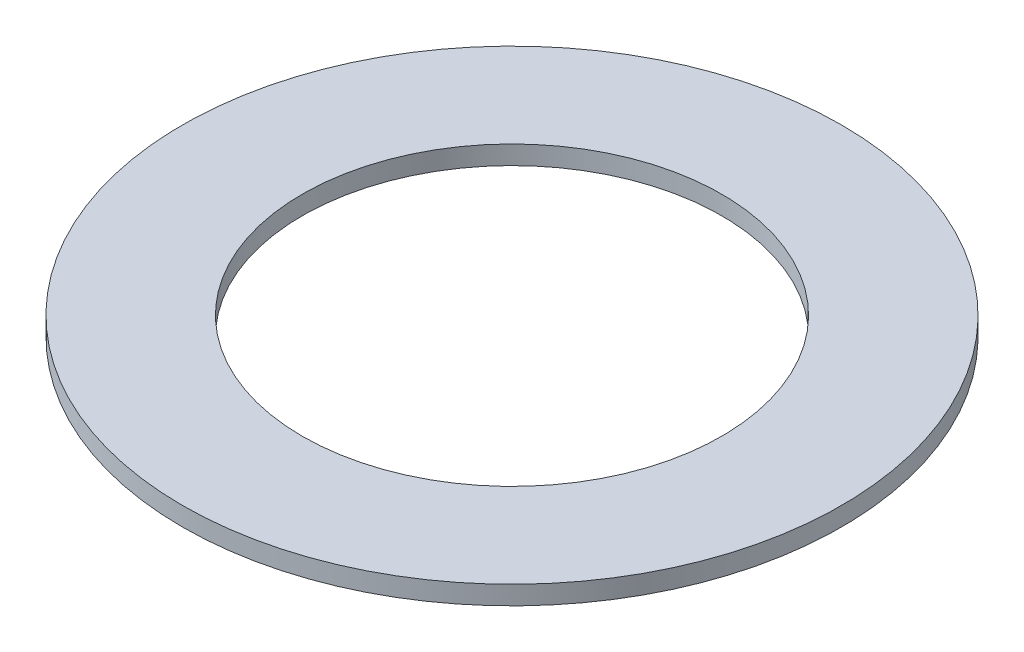
SolidWorks part; units mm, degrees
material "Chrome Stainless Steel"
ref_plane "Front Plane" through (0, 0, 0) normal (0, 0, 1) x (1, 0, 0)
ref_plane "Top Plane" through (0, 0, 0) normal (0, 1, 0) x (1, 0, 0)
ref_plane "Right Plane" through (0, 0, 0) normal (1, 0, 0) x (0, 0, -1)
sketch "Sketch1" plane through (0, 0, 0) normal (0, 1, 0) x (1, 0, 0)
  circle A0 centre (0, 0) radius 2.8
  circle A1 centre (0, 0) radius 4.4
  dimension "D1" = 5.6
  dimension "D2" = 8.8
extrude "Boss-Extrude1" add sketch "Sketch1" along normal mid plane 0.25
